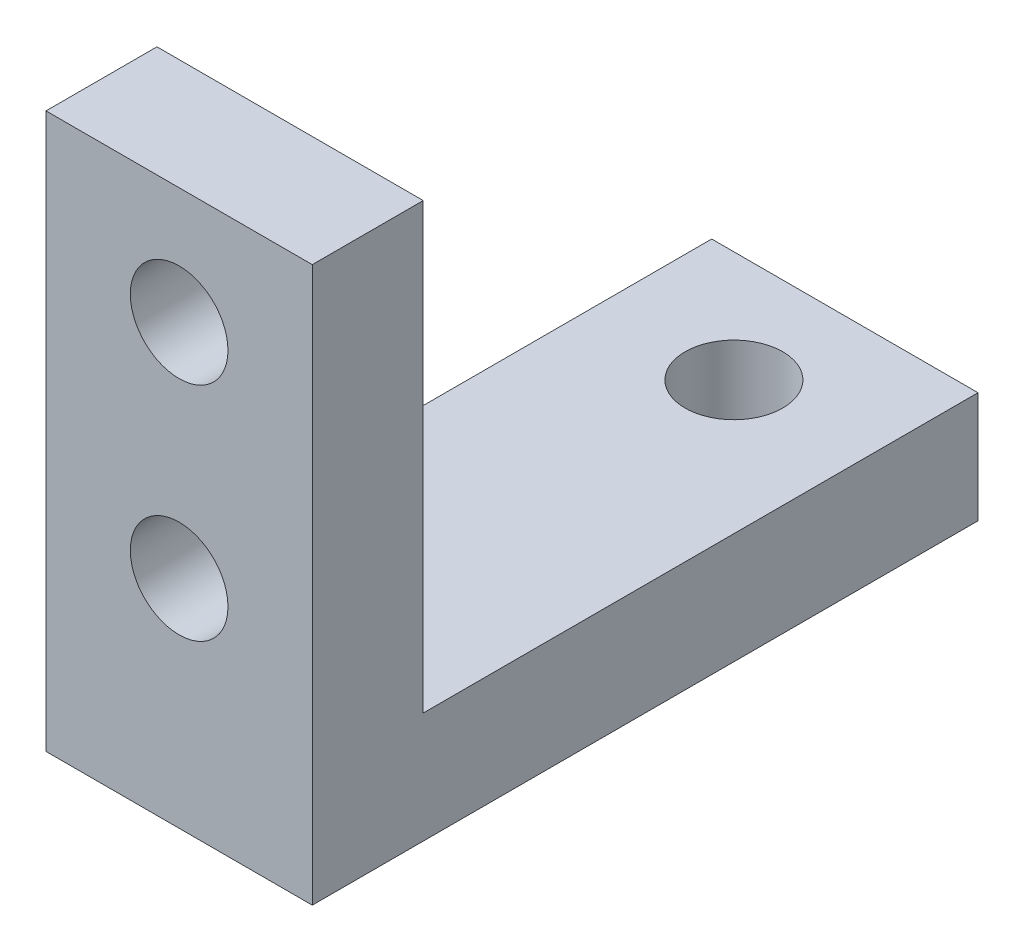
SolidWorks part; units mm, degrees
ref_plane "Front Plane" through (0, 0, 0) normal (0, 0, 1) x (1, 0, 0)
ref_plane "Top Plane" through (0, 0, 0) normal (0, 1, 0) x (1, 0, 0)
ref_plane "Right Plane" through (0, 0, 0) normal (1, 0, 0) x (0, 0, -1)
sketch "Sketch1" plane through (0, 0, 0) normal (1, 0, 0) x (0, 0, -1)
  line L1 (0, 0) -> (5, 0)
  line L2 (0, 0) -> (0, 25)
  line L3 (0, 25) -> (5, 25)
  line L4 (5, 0) -> (5, 25)
  line L5 (0, 0) -> (30, 0)
  line L6 (0, 0) -> (0, 5)
  line L7 (0, 5) -> (30, 5)
  line L8 (30, 0) -> (30, 5)
  dimension "D1" = 25
  dimension "D2" = 5
  dimension "D3" = 30
  dimension "D4" = 5
extrude "Boss-Extrude1" add sketch "Sketch1" along normal blind 12 contours L2 L7 L4 L3 | L7 L2 L1 L4 | L5 L8 L7 L4
sketch "Sketch2" plane through (0, 0, -5) normal (0, 0, -1) x (-1, 0, 0)
  line L0 (-6, 25) -> (-6, 5) construction
  line L1 (-12, 25) -> (0, 25) construction
  line L2 (-12, 5) -> (0, 5) construction
  circle A0 centre (-6, 19.75) radius 2.2
  circle A1 centre (-6, 9.75) radius 2.2
  dimension "D1" = 4.4
  dimension "D2" = 4.4
  dimension "D3" = 5.25
  dimension "D4" = 10
extrude "Cut-Extrude1" cut sketch "Sketch2" against normal blind 12
sketch "Sketch3" plane through (0, 0, 0) normal (0, -1, 0) x (1, 0, 0)
  line L0 (6, 0) -> (6, -30) construction
  line L1 (12, 0) -> (0, 0) construction
  line L2 (12, -30) -> (0, -30) construction
  circle A0 centre (6, -25) radius 2.2
  circle A1 centre (6, -2.5) radius 2.2
  dimension "D1" = 4.4
  dimension "D2" = 4.4
  dimension "D3" = 25
  dimension "D4" = 22.5
extrude "Cut-Extrude3" cut sketch "Sketch3" against normal blind 5 contours L0 A0 | A0 L0
